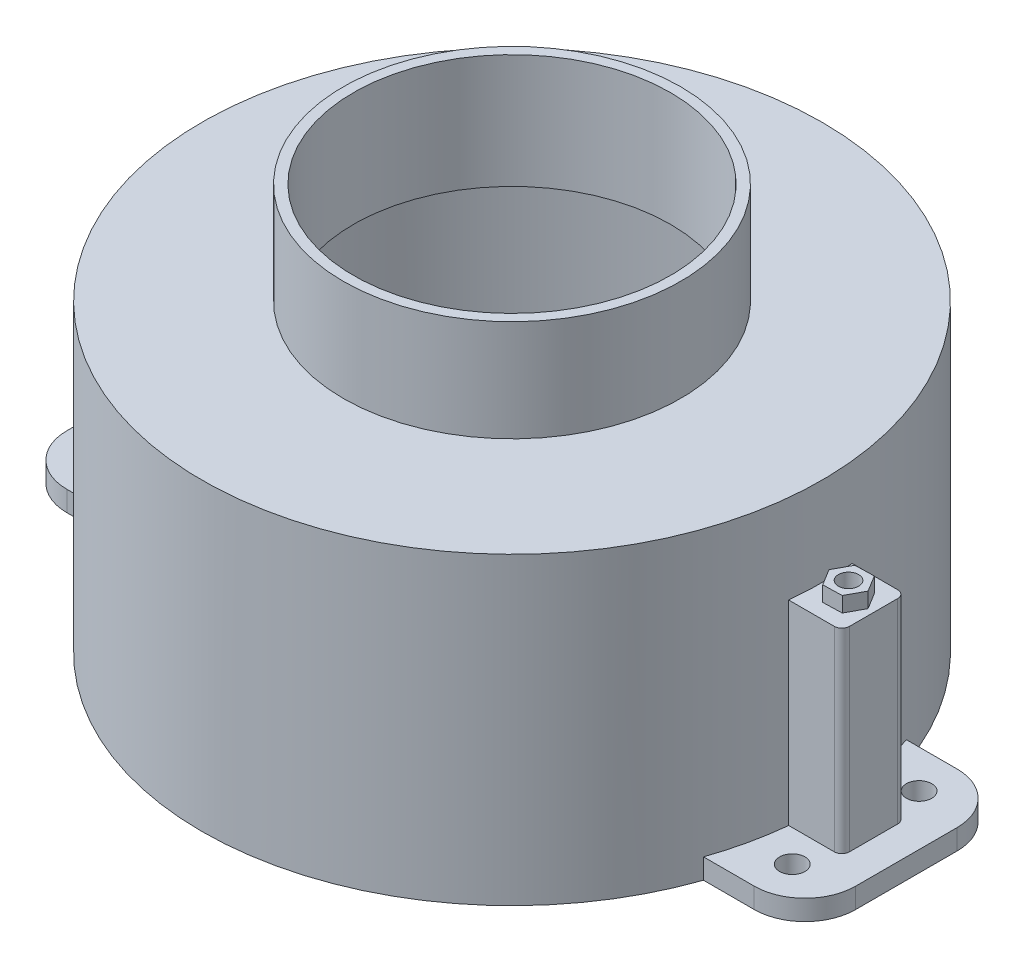
SolidWorks part; units mm, degrees
other "DetailItem1"
other "Weld Folder"
other "Weld Bead1"
ref_plane "Front Plane" through (0, 0, 0) normal (0, 0, 1) x (1, 0, 0)
ref_plane "Top Plane" through (0, 0, 0) normal (0, 1, 0) x (1, 0, 0)
ref_plane "Right Plane" through (0, 0, 0) normal (1, 0, 0) x (0, 0, -1)
sketch "Sketch1" plane through (0, 0, 0) normal (0, 0, 1) x (1, 0, 0)
  line L0 (-122.25, -160) -> (-118.25, -160)
  line L1 (-118.25, -160) -> (-118.25, -153)
  line L2 (-118.25, -153) -> (-115.25, -153)
  line L7 (-115.25, -153) -> (-115.25, -45)
  line L9 (-122.25, -40) -> (-122.25, -160)
  line L10 (0, -155) -> (0, 131.3181) construction
  line L11 (-122.25, -40) -> (-66.5, -40)
  line L12 (-66.5, -40) -> (-66.5, 0)
  line L13 (-62.5, 0) -> (-62.5, -45)
  line L14 (-62.5, -45) -> (-115.25, -45)
  line L15 (-62.5, 0) -> (-66.5, 0)
  dimension "D1" = 244.5
  dimension "D3" = 4
  dimension "D4" = 7
  dimension "D6" = 2
  dimension "D2" = 7
  dimension "D7" = 4
  dimension "D8" = 133
  dimension "D9" = 5
  dimension "D10" = 40
  dimension "D5" = 120
revolve "Revolve1" add sketch "Sketch1" angle 360 about L10
chamfer "Chamfer1" distance 1 angle 45 2 edges at (0, -153, -115.25) (0, -160, -118.25)
sketch "Sketch3" plane through (0, 0, 0) normal (1, 0, 0) x (0, 0, -1)
  line L0 (0, -160) -> (0, -90) construction
  line L1 (-11, -160) -> (-11, -90)
  line L2 (11, -160) -> (11, -90)
  line L3 (-122.25, -160) -> (122.25, -160) construction
  arc A0 (-11, -160) -> (11, -160) centre (0, -160) ccw
  arc A1 (11, -90) -> (-11, -90) centre (0, -90) ccw
  point P3 (0, -125)
  dimension "D1" = 22
  dimension "D2" = 70
extrude "Cut-Extrude1" cut sketch "Sketch3" against normal through all both and the other way through all
sketch "Sketch2" plane through (34.6529, 0, -427.9463) normal (0, 1, 0) x (1, 0, 0)
  line L0 (107.9346, -440.4463) -> (106.4346, -438.9463) construction
  line L1 (82.9346, -415.4463) -> (107.9346, -415.4463)
  line L2 (82.9346, -415.4463) -> (82.9346, -440.4463)
  line L3 (82.9346, -440.4463) -> (107.9346, -440.4463)
  line L4 (107.9346, -415.4463) -> (107.9346, -440.4463)
  line L5 (106.4346, -438.9463) -> (80.071, -438.9463)
  line L6 (106.4346, -438.9463) -> (106.4346, -416.9463)
  line L7 (106.4346, -416.9463) -> (80.071, -416.9463)
  line L8 (80.071, -438.9463) -> (80.071, -416.9463)
  line L9 (106.4346, -416.9463) -> (107.9346, -415.4463) construction
  circle A0 centre (-34.6529, -427.9463) radius 118.25 construction
  circle A1 centre (-34.6529, -427.9463) radius 115.25 construction
  point P4 (82.9346, -427.9463)
  dimension "D1" = 25
  dimension "D2" = 1.5
  dimension "D3" = 1.5
extrude "Boss-Extrude2" add sketch "Sketch2" along normal blind 85 from surface at -160 contours L7 L6 L5 L2 L3 L4 L1 starting at face at (0, -160, 65.875)
sketch "Sketch5" plane through (0, -75, 0) normal (0, 1, 0) x (1, 0, 0)
  line L0 (141.0875, 11) -> (121.7541, 11) construction
  line L1 (141.0875, -11) -> (141.0875, 11) construction
  line L2 (141.0875, -11) -> (121.7541, -11) construction
  line L3 (141.0875, 11) -> (121.7541, 11)
  line L4 (141.0875, -11) -> (141.0875, 11)
  line L5 (141.0875, -11) -> (121.7541, -11)
  circle A0 centre (0, 0) radius 122.25 construction
  circle A1 centre (0, 0) radius 122.25
  line M6 (121.7541, 11) -> (141.0875, 11)
  line M7 (141.0875, 11) -> (141.0875, -11)
  line M8 (141.0875, -11) -> (121.7541, -11)
extrude "Boss-Extrude3" add sketch "Sketch5" against normal blind 3 contours A1 M8 M7 M6
fillet "Fillet1" radius 1.5 2 edges at (141.0875, -119, -11) (141.0875, -119, 11)
fillet "Fillet2" radius 3 2 edges at (142.5875, -117.5, -12.5) (142.5875, -117.5, 12.5)
mirror "Mirror1" about plane through (0, 0, 0) normal (1, 0, 0) of "Boss-Extrude2", "Boss-Extrude3", "Fillet1", "Fillet2"
sketch "Sketch6" plane through (0, -160, 0) normal (0, -1, 0) x (1, 0, 0)
  line L0 (0, 0) -> (-171.2075, 0) construction
  line L1 (-155.5208, -40) -> (-115.5208, -40)
  line L2 (-155.5208, -40) -> (-155.5208, 40)
  line L3 (-155.5208, 40) -> (-115.5208, 40)
  line L4 (-115.5208, -40) -> (-115.5208, 40)
  line L5 (0, 0) -> (0, 138.1878) construction
  line L6 (155.5208, 40) -> (115.5208, 40)
  line L7 (115.5208, -40) -> (115.5208, 40)
  line L8 (155.5208, -40) -> (155.5208, 40)
  line L9 (155.5208, -40) -> (115.5208, -40)
  circle A0 centre (0, 0) radius 122.25
  circle A1 centre (-135.5208, 25) radius 5
  circle A2 centre (-135.5208, -25) radius 5
  circle A3 centre (135.5208, -25) radius 5
  circle A4 centre (135.5208, 25) radius 5
  point P9 (-115.5208, 0)
  line M26 (-142.5875, 9.5) -> (-142.5875, -9.5)
  arc M27 (-142.5875, -9.5) -> (-139.5875, -12.5) centre (-139.5875, -9.5) ccw
  line M28 (-139.5875, -12.5) -> (-121.6093, -12.5)
  arc M29 (-121.6093, -12.5) -> (121.6093, -12.5) centre (0, 0) ccw
  line M30 (121.6093, -12.5) -> (139.5875, -12.5)
  arc M31 (139.5875, -12.5) -> (142.5875, -9.5) centre (139.5875, -9.5) ccw
  line M32 (142.5875, -9.5) -> (142.5875, 9.5)
  arc M33 (142.5875, 9.5) -> (139.5875, 12.5) centre (139.5875, 9.5) ccw
  line M34 (139.5875, 12.5) -> (121.6093, 12.5)
  arc M35 (121.6093, 12.5) -> (-121.6093, 12.5) centre (0, 0) ccw
  line M36 (-121.6093, 12.5) -> (-139.5875, 12.5)
  arc M37 (-139.5875, 12.5) -> (-142.5875, 9.5) centre (-139.5875, 9.5) ccw
  dimension "D1" = 244.5
  dimension "D4" = 10
  dimension "D2" = 40
  dimension "D3" = 80
  dimension "D5" = 20
  dimension "D6" = 15
extrude "Boss-Extrude4" add sketch "Sketch6" against normal blind 8 contours L3 L2 L1 A2 A1 M29 M28 M27 M26 M37 M36 M35 | L9 L8 L6 A3 A4 M35 M34 M33 M32 M31 M30 M29
fillet "Fillet3" radius 20 4 edges at (-155.5208, -156, -40) (-155.5208, -156, 40) (155.5208, -156, 40) (155.5208, -156, -40)
sketch "Sketch7" plane through (0, -75, 0) normal (0, 1, 0) x (1, 0, 0)
  circle A0 centre (-132.6999, 0) radius 4
  dimension "D1" = 8
extrude "Cut-Extrude2" cut sketch "Sketch7" against normal blind 10
sketch "Sketch8" plane through (0, -75, 0) normal (0, 1, 0) x (1, 0, 0)
  line L1 (-128.7707, 6.3949) -> (-136.2734, 6.6002)
  line L2 (-136.2734, 6.6002) -> (-140.2026, 0.2053)
  line L3 (-140.2026, 0.2053) -> (-136.629, -6.3949)
  line L4 (-136.629, -6.3949) -> (-129.1263, -6.6002)
  line L5 (-129.1263, -6.6002) -> (-125.1971, -0.2053)
  line L6 (-125.1971, -0.2053) -> (-128.7707, 6.3949)
  circle A0 centre (-132.6999, 0) radius 6.5 construction
  circle A1 centre (-132.6999, 0) radius 4
  dimension "D2" = 8
  dimension "D1" = 13
extrude "Boss-Extrude5" add sketch "Sketch8" along normal blind 6
mirror "Mirror2" about plane through (0, 0, 0) normal (1, 0, 0) of "Boss-Extrude5", "Cut-Extrude2"
equation "\"d_ext_rouleau\"= 90"
equation "\"epaisseur_rouleau\"=80"
equation "\"alesage-rouleau\"= 52"
equation "\"jeu_dent_rouleau\"= 2"
equation "\"profondeur_dent_rouleau\"=4"
equation "\"n_dent_roueau\"= 15"
equation "\"d_ext_roulement_rouleau\"= 42"
equation "\"d_int_roulement_rouleau\"= 20"
equation "\"B_roulement_rouleau\"= 12"
equation "\"r_roulement_rouleau\"= 0.6"
equation "\"d_bille_roulement_rouleau\"= 8"
equation "\"F_anneau_alesage_rouleau\"=1.85"
equation "\"G_anneau_alesage_rouleau\"=47.5"
equation "\"K_anneau_alesage_rouleau\"=3.75"
equation "\"d_vis_flasque_rouleau\"=5"
equation "\"l-x_vis_flasque_rouleau\"=4"
equation "\"g_anneau_arbre_rouleau\"=19"
equation "\"f_anneau_arbre_rouleau\"=1.3"
equation "\"k_anneau_arbre_rouleau\"=1.5"
equation "\"entrax_vis_rouleau\"=65"
equation "\"d_granulat\"= 8"
equation "\"h_matrice\"= 22"
equation "\"d_matrice\"= 220"
equation "\"zone_vide_matrice\" = 48"
equation "\"d_alesage_matrice\"=20"
equation "\"a_clavette_alesage_matrice\"=6"
equation "\"B_roulement_matrice\"= 12"
equation "\"d_ext_roulement_matrice\"= 42"
equation "\"d_int_roulement_matrice\"= 20"
equation "\"r_roulement_matrice\"= 1"
equation "\"h_epaulement_arbre_matrice\" = 80"
equation "\"j_clavette_arbre_matrice\" = 6"
equation "\"g_anneaux_arbre_matrice\" = 19"
equation "\"f_anneaux_arbre_matrice\" = 1.3"
equation "\"B_roulement_bc_arbre_matrice\"= 10"
equation "\"e_anneaux_arbre_matrice\" = 1.2"
equation "\"h_polie_matrice\" = 40"
equation "\"l_arbre_matrice\" = 300"
equation "\"d_int_ecrou_encouch_matrice\" = 20"
equation "\"d_ext_ecrou_encouch_matrice\" = 32"
equation "\"b_ecrou_encouch_matrice\" = 6"
equation "\"s_ecrou_encouch_matrice\" = 4"
equation "\"G_ecrou_encouch_matrice\" = 1"
equation "\"E_ecrou_encouch_matrice\" = 4"
equation "\"d_int_roulement_conique_matrice\"=25"
equation "\"d_ext_roulement_conique_matrice\"=52"
equation "\"b_roulement_conique_matrice\"=16.25"
equation "\"d_int_roulement_bc_matrice\"=20"
equation "\"d_ext_roulement_bc_matrice\"=42"
equation "\"b_roulement_bc_matrice\" = 12"
equation "\"d_tube_sup_carter\"=244.5"
equation "\"e_tube_sup_carter\"=12"
equation "\"d_tube_inf_catrer\"= 168.3"
equation "\"e_tube_inf_carter\"= 6"
equation "\"D1@Sketch1\" = \"d_tube_inf_carter_cache\""
equation "\"d_tube_inf_carter_cache\" = 244.5"
equation "\"e_tube_inf_carter_cache\" = 8"
equation "\"D2@Sketch1\"=\"e_tube_inf_carter_cache\"-1"
equation "\"e_tube_sup_carter_cache\" = 4"
equation "\"D7@Sketch1\"=\"e_tube_sup_carter_cache\""
equation "\"d_tube_sup_carter_cache\" = 133"
equation "\"D8@Sketch1\"=\"d_tube_sup_carter_cache\""
equation "\"h_tube_trimee\" = 40"
equation "\"D10@Sketch1\"=\"h_tube_trimee\""
equation "\"D2@Sketch3\"=\"d_ext_rouleau\"-20"
equation "\"D1@Sketch6\"=\"d_tube_inf_carter_cache\""
